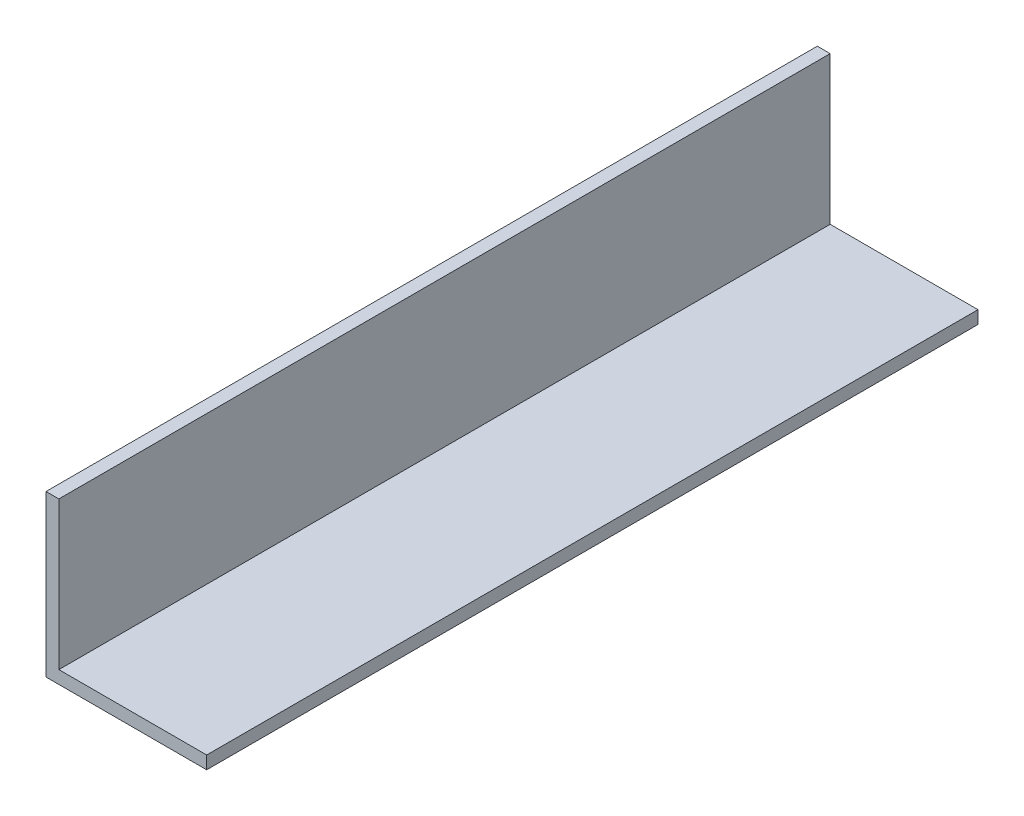
SolidWorks part; units mm, degrees
ref_plane "Front Plane" through (0, 0, 0) normal (0, 0, 1) x (1, 0, 0)
ref_plane "Top Plane" through (0, 0, 0) normal (0, 1, 0) x (1, 0, 0)
ref_plane "Right Plane" through (0, 0, 0) normal (1, 0, 0) x (0, 0, -1)
sketch "Sketch1" plane through (0, 0, 0) normal (0, 0, 1) x (1, 0, 0)
  line L0 (0, 0) -> (25, 0)
  line L1 (25, 0) -> (25, 2)
  line L2 (25, 2) -> (2, 2)
  line L3 (2, 2) -> (2, 25)
  line L4 (2, 25) -> (0, 25)
  line L5 (0, 25) -> (0, 0)
  dimension "D1" = 25
  dimension "D2" = 25
  dimension "D3" = 2
  dimension "D4" = 2
extrude "Boss-Extrude1" add sketch "Sketch1" along normal blind 120
